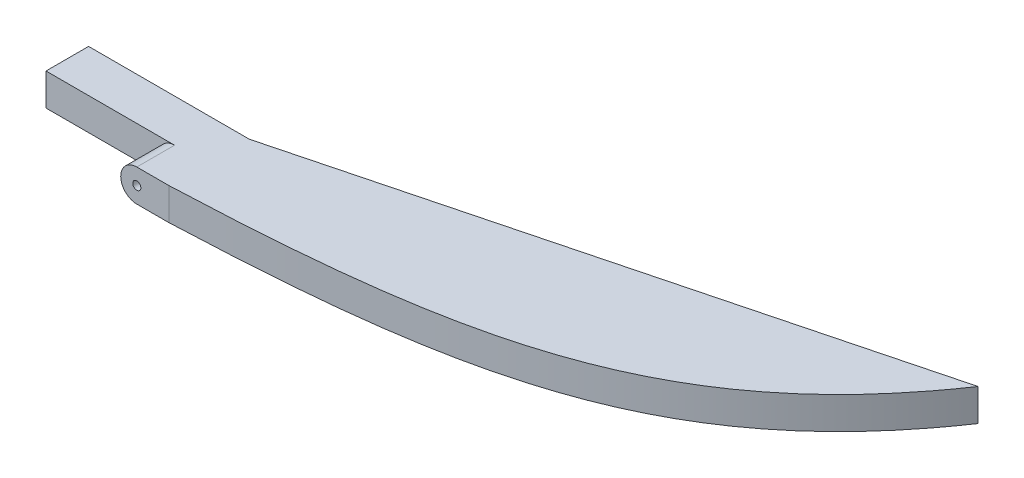
SolidWorks part; units mm, degrees
ref_plane "Alzado" through (0, 0, 0) normal (0, 0, 1) x (1, 0, 0)
ref_plane "Planta" through (0, 0, 0) normal (0, 1, 0) x (1, 0, 0)
ref_plane "Vista lateral" through (0, 0, 0) normal (1, 0, 0) x (0, 0, -1)
sketch "Croquis2" plane through (0, 0, 0) normal (0, 1, 0) x (1, 0, 0)
  line L0 (0, 0) -> (90, 0) construction
  line L1 (0, 0) -> (0, 12.5)
  line L2 (90, 0) -> (90, 39) construction
  line L3 (0, 12.5) -> (90, 35.8654)
  spline S0 degree 4 poles (-9.0097, -0.3032) (-8.7076, -0.2945) (-8.1243, -0.2777) (-7.1409, -0.2505) (-5.1439, -0.1858) (-3.7083, -0.1414) (-0.7618, -0.0308) (0.4754, 0.0183) (2.9924, 0.1252) (4.5799, 0.2009) (6.6126, 0.3012) (8.3923, 0.3988) (10.3159, 0.5099) (12.159, 0.6263) (14.5117, 0.7852) (17.3057, 0.9943) (20.1144, 1.2315) (22.9099, 1.4998) (25.7075, 1.7965) (29.4305, 2.2324) (34.4573, 2.9285) (39.9176, 3.8881) (45.327, 5.1051) (49.7699, 6.3191) (53.3462, 7.448) (56.8702, 8.731) (60.3296, 10.1801) (63.7103, 11.8049) (66.9976, 13.6115) (70.1773, 15.6016) (72.8543, 17.5009) (75.0672, 19.2371) (76.8547, 20.7526) (78.2502, 22.0046) (79.6197, 23.3032) (80.9624, 24.6475) (82.2773, 26.0361) (83.4032, 27.2889) (84.3454, 28.3827) (85.1155, 29.3069) (85.7227, 30.0536) (86.321, 30.8074) (86.9107, 31.5683) (87.4913, 32.335) (88.0643, 33.1098) (88.6299, 33.8921) (89.0999, 34.5557) (89.557, 35.2158) (89.908, 35.7289) (90.1259, 36.0512) (90.5206, 36.6414) (91.018, 37.3961) (91.5196, 38.1766) (92.1613, 39.1955) (92.8125, 40.2583) (93.4957, 41.4026) (94.1961, 42.6106) (94.7128, 43.5262) (95.0517, 44.1381) (95.2199, 44.4446) knots 0 0 0 0 0 0.009353 0.018706 0.037411 0.056117 0.074823 0.090398 0.105974 0.121549 0.137125 0.1527 0.168276 0.183851 0.199426 0.230577 0.261728 0.277304 0.292879 0.32403 0.386332 0.445925 0.477075 0.508226 0.539377 0.570528 0.601679 0.63283 0.66398 0.695131 0.726282 0.741858 0.757433 0.773009 0.788584 0.804577 0.82057 0.836563 0.844559 0.852555 0.860552 0.868548 0.876545 0.884541 0.892538 0.900535 0.908531 0.912529 0.916528 0.921147 0.925767 0.935007 0.944247 0.953487 0.965115 0.976743 0.988372 1 1 1 1 1 construction
  spline S1 degree 4 poles (0, 0) (0.3941, 0.0158) (1.195, 0.0488) (2.9924, 0.1252) (4.5799, 0.2009) (6.6126, 0.3012) (8.3923, 0.3988) (10.3159, 0.5099) (12.159, 0.6263) (14.5117, 0.7852) (17.3057, 0.9943) (20.1144, 1.2315) (22.9099, 1.4998) (25.7075, 1.7965) (29.4305, 2.2324) (34.4573, 2.9285) (39.9176, 3.8881) (45.327, 5.1051) (49.7699, 6.3191) (53.3462, 7.448) (56.8702, 8.731) (60.3296, 10.1801) (63.7103, 11.8049) (66.9976, 13.6115) (70.1773, 15.6016) (72.8543, 17.5009) (75.0672, 19.2371) (76.8547, 20.7526) (78.2502, 22.0046) (79.6197, 23.3032) (80.9624, 24.6475) (82.2773, 26.0361) (83.4032, 27.2889) (84.3454, 28.3827) (85.1155, 29.3069) (85.7227, 30.0536) (86.321, 30.8074) (86.9107, 31.5683) (87.4913, 32.335) (88.0643, 33.1098) (88.6299, 33.8921) (89.0999, 34.5557) (89.557, 35.2158) (89.8293, 35.6139) (89.9432, 35.7816) (90, 35.8654) knots 0.074823 0.074823 0.074823 0.074823 0.074823 0.090398 0.105974 0.121549 0.137125 0.1527 0.168276 0.183851 0.199426 0.230577 0.261728 0.277304 0.292879 0.32403 0.386332 0.445925 0.477075 0.508226 0.539377 0.570528 0.601679 0.63283 0.66398 0.695131 0.726282 0.741858 0.757433 0.773009 0.788584 0.804577 0.82057 0.836563 0.844559 0.852555 0.860552 0.868548 0.876545 0.884541 0.892538 0.900535 0.908531 0.912529 0.916528 0.916528 0.916528 0.916528 0.916528
  dimension "D1" = 35.8654
  dimension "D2" = 12.5
  dimension "D3" = 90
extrude "Saliente-Extruir1" add sketch "Croquis2" along normal blind 5
sketch "Croquis3" plane through (0, 0, 0) normal (-1, 0, 0) x (0, 0, 1)
  line L0 (0, 5) -> (0, 0) construction
  line L1 (-12.5, 0) -> (0, 0)
  line L2 (-12.5, 0) -> (-12.5, 5)
  line L3 (-12.5, 5) -> (0, 5)
  line L4 (0, 0) -> (0, 5)
  line L5 (-12.5, 0) -> (0, 5) construction
  line L6 (-12.5, 5) -> (0, 0) construction
  line L7 (-12.5, 2.5) -> (0, 2.5) construction
  line L8 (-12.5, 5) -> (-12.5, 0) construction
  point P0 (-6.25, 2.5)
  dimension "D1" = 12.5
  dimension "D2" = 5
extrude "Saliente-Extruir2" add sketch "Croquis3" along normal blind 25
sketch "Croquis6" plane through (0, 0, 0) normal (0, 0, 1) x (1, 0, 0)
  line L0 (-5, 2.5) -> (-25, 2.5) construction
  line L2 (-25, 0) -> (-25, 5) construction
  circle A0 centre (-5, 2.5) radius 0.63
  dimension "D1" = 20
  dimension "D2" = 1.26
extrude "Cortar-Extruir3" cut sketch "Croquis6" against normal blind 1.5
sketch "Croquis5" plane through (0, 0, 0) normal (0, 0, 1) x (1, 0, 0)
  line L4 (-25, 5) -> (0, 5) construction
  line L5 (-25, 0) -> (-25, 5)
  line L6 (-25, 0) -> (0, 0) construction
  line L7 (-34.55, 0) -> (-25, 0)
  line L8 (-25, 5) -> (-5, 5)
  circle A0 centre (-5, 2.5) radius 2.5
  line M8 (0, 5) -> (-25, 5)
  line M9 (-25, 5) -> (-25, 0)
  line M10 (-25, 0) -> (0, 0)
  dimension "D2" = 5
extrude "Cortar-Extruir4" cut sketch "Croquis5" against normal blind 5.875 contours A0 M8 M9 M10
equation "\"A_ALETA\"= ( ( ( tan ( \"ANG_ALETA\" ) ) * \"L_ALETA\" ) + \"A_BASE\" - ( \"GAP_ALETAS\" / 2 ) )"
equation "\"A_CAJA\"= ( 2 * \"A_BASE\" ) + \"GAP_ALETAS\""
equation "\"D1@Croquis2\" = \"A_BASE\""
equation "\"L_ALETA\"=90.000000"
equation "\"D3@Croquis2\" = \"L_ALETA\""
equation "\"TAU_ALETA\"= ( \"L_ALETA\" / ( log ( ( \"A_ALETA\" ) + 1 ) ) )"
equation "\"E_ALETA\"=5.000000"
equation "\"R_SONDA\"= 2.05"
equation "\"D_SONDA\"=20.000000"
equation "\"L_CAJA\"=25.000000"
equation "\"D2@Croquis2\"=\"A_BASE\""
equation "\"D1@Saliente-Extruir1\"=\"E_ALETA\""
equation "\"D1@Croquis3\"=\"A_BASE\""
equation "\"D1@Saliente-Extruir2\"=\"L_CAJA\""
equation "\"A_BASE\"= ( \"L_DIE\" - \"E_CAJA\" )"
equation "\"E_CAJA\"= 2.5"
equation "\"W_CAJA\"= \"A_CAJA\" * \"CONST_CAJA\""
equation "\"W_CONC\"= ( \"W_CAJA\" / \"CONST_CONC\" ) "
equation "\"A_CONC\"= ( \"A_CAJA\" / \"CONST_CONC\" )"
equation "\"L_CONC\"= \"D_SONDA\" - \"OFFSET_CONC\""
equation "\"W_ALETA\"=70.000000"
equation "\"GAP_ALETAS\"=1.500000"
equation "\"L_DIE_SONDA\"= ( \"GAP_ALETAS\" / 4 )"
equation "\"D1@Croquis5\" = \"L_CONC\""
equation "\"D1@Cortar-Extruir2\" = \"A_BASE\" - ( ( \"A_CAJA\" - \"A_CONC\" ) / 2 )"
equation "\"CONST_CONC\"=2.000000"
equation "\"K\"= 1.5"
equation "\"L_DIE\"= 15"
equation "\"L_CI\"= 18"
equation "\"D1@Croquis6\" = \"D_SONDA\""
equation "\"D2@Croquis6\" = \"R_C_SONDA\" * 2"
equation "\"D1@Cortar-Extruir3\" = \"L_CI\" - \"E_CAJA\" - \"A_BASE\" - \"GAP_ALETAS\""
equation "\"CONST_CAJA\"=2.000000"
equation "\"ANG_ALETA\"=15.000000"
equation "\"D1@Cortar-Extruir4\" = \"A_BASE\" - ( ( \"A_CAJA\" - \"A_CONC\" ) / 2 )"
equation "\"R_C_SONDA\"= 0.63"
equation "\"TOLERANCIA\"= 0.1"
equation "\"OFFSET_CONC\"= ( 2 * \"R_TORNILLO\" )"
equation "\"R_TORNILLO\"=2.600000"
equation "\"D2@Croquis3\" = \"E_ALETA\""
